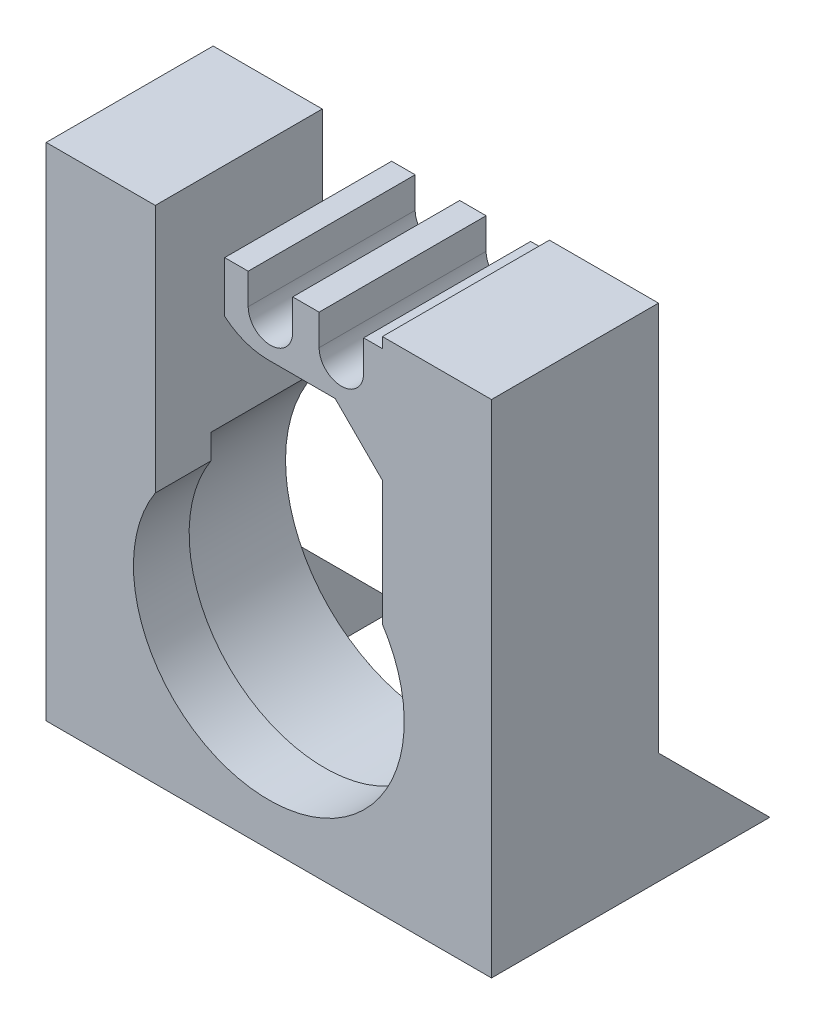
SolidWorks part; units mm, degrees
ref_plane "前视基准面" through (0, 0, 0) normal (0, 0, 1) x (1, 0, 0)
ref_plane "上视基准面" through (0, 0, 0) normal (0, 1, 0) x (1, 0, 0)
ref_plane "右视基准面" through (0, 0, 0) normal (1, 0, 0) x (0, 0, -1)
sketch "草图2" plane through (0, 0, 0) normal (0, 0, 1) x (1, 0, 0)
  line L2 (13.103, 56.3875) -> (13.103, 11.3875)
  line L3 (13.103, 11.3875) -> (53.103, 11.3875)
  line L4 (53.103, 56.3875) -> (53.103, 11.3875)
  line L5 (33.103, 52.7334) -> (33.103, -4.3239) construction
  line L7 (22.9017, 36.2386) -> (22.9017, 56.3875)
  line L8 (22.9017, 56.3875) -> (13.103, 56.3875)
  line L9 (43.3043, 36.2386) -> (43.3043, 56.3875)
  line L10 (43.3043, 56.3875) -> (53.103, 56.3875)
  arc A1 (22.9017, 36.2386) -> (43.3043, 36.2386) centre (33.103, 27.3965) ccw
  circle A4 centre (33.103, 27.3965) radius 13.5 construction
  dimension "D2" = 45
  dimension "D1" = 40
extrude "凸台-拉伸1" add sketch "草图2" along normal blind 10
sketch "草图3" plane through (0, 0, 10) normal (0, 0, 1) x (1, 0, 0)
  line L0 (13.103, 56.3875) -> (22.9017, 56.3875)
  line L1 (22.9017, 56.3875) -> (22.9017, 34.0146)
  line L2 (13.103, 56.3875) -> (13.103, 11.3875)
  line L3 (13.103, 11.3875) -> (53.103, 11.3875)
  line L4 (53.103, 11.3875) -> (53.103, 56.3875)
  line L5 (53.103, 56.3875) -> (43.3043, 56.3875)
  line L6 (43.3043, 56.3875) -> (43.3043, 34.0146)
  circle A0 centre (33.103, 27.3965) radius 12.16 construction
  arc A1 (22.9017, 34.0146) -> (43.3043, 34.0146) centre (33.103, 27.3965) ccw
extrude "凸台-拉伸2" add sketch "草图3" along normal blind 5
sketch "草图4" plane through (53.103, 0, 0) normal (1, 0, 0) x (0, 0, -1)
  line L0 (0, 21.3875) -> (10, 11.3875)
  line L1 (0, 11.3875) -> (0, 56.3875) construction
  line L2 (-85.3164, 11.3875) -> (109.817, 11.3875) construction
  line L3 (10, 11.3875) -> (0, 11.3875)
  line L4 (0, 11.3875) -> (0, 21.3875)
  dimension "D1" = 10
  dimension "D2" = 10
extrude "凸台-拉伸3" add sketch "草图4" against normal blind 7
sketch "草图5" plane through (13.103, 0, 0) normal (-1, 0, 0) x (0, 0, 1)
  line L0 (0, 11.3875) -> (-10, 11.3875) construction
  line L1 (-10, 11.3875) -> (0, 21.3875) construction
  line L2 (0, 11.3875) -> (-10, 11.3875)
  line L3 (-10, 11.3875) -> (0, 21.3875)
  line L4 (0, 21.3875) -> (0, 11.3875)
extrude "凸台-拉伸4" add sketch "草图5" against normal blind 7 separate body
sketch "草图6" plane through (0, 0, 15) normal (0, 0, 1) x (1, 0, 0)
  line L0 (43.3043, 45.2011) -> (39.0617, 49.4437)
  line L1 (43.3043, 56.3875) -> (43.3043, 34.0146) construction
  line L2 (39.0617, 49.4437) -> (33.0254, 49.4437)
  line L3 (23.5574, 55.4437) -> (27.0254, 55.4437) construction
  line L4 (29.1361, 55.4437) -> (31.2469, 55.4437)
  line L5 (31.2469, 55.4437) -> (31.2469, 52.6792)
  line L6 (35.2469, 52.6792) -> (35.2469, 55.4437)
  line L7 (35.2469, 55.4437) -> (37.6194, 55.4437)
  line L8 (37.6194, 55.4437) -> (37.6194, 52.6792)
  line L9 (41.6194, 52.6792) -> (41.6194, 55.4437)
  line L10 (41.6194, 55.4437) -> (43.3043, 55.4437)
  line L11 (43.3043, 55.4437) -> (43.3043, 45.2011)
  line L12 (29.1361, 55.4437) -> (29.1361, 50.8749)
  line L13 (29.1361, 55.4437) -> (42.811, 55.4437) construction
  arc A0 (33.0254, 49.4437) -> (29.1361, 50.8749) centre (33.0254, 55.4437) cw
  arc A1 (31.2469, 52.6792) -> (35.2469, 52.6792) centre (33.2469, 52.6792) ccw
  arc A2 (37.6194, 52.6792) -> (41.6194, 52.6792) centre (39.6194, 52.6792) ccw
  dimension "D1" = 4
  dimension "D2" = 4
extrude "凸台-拉伸5" add sketch "草图6" against normal up to surface (15 mm away) up to face at (35.703, 34.1235, 0)
